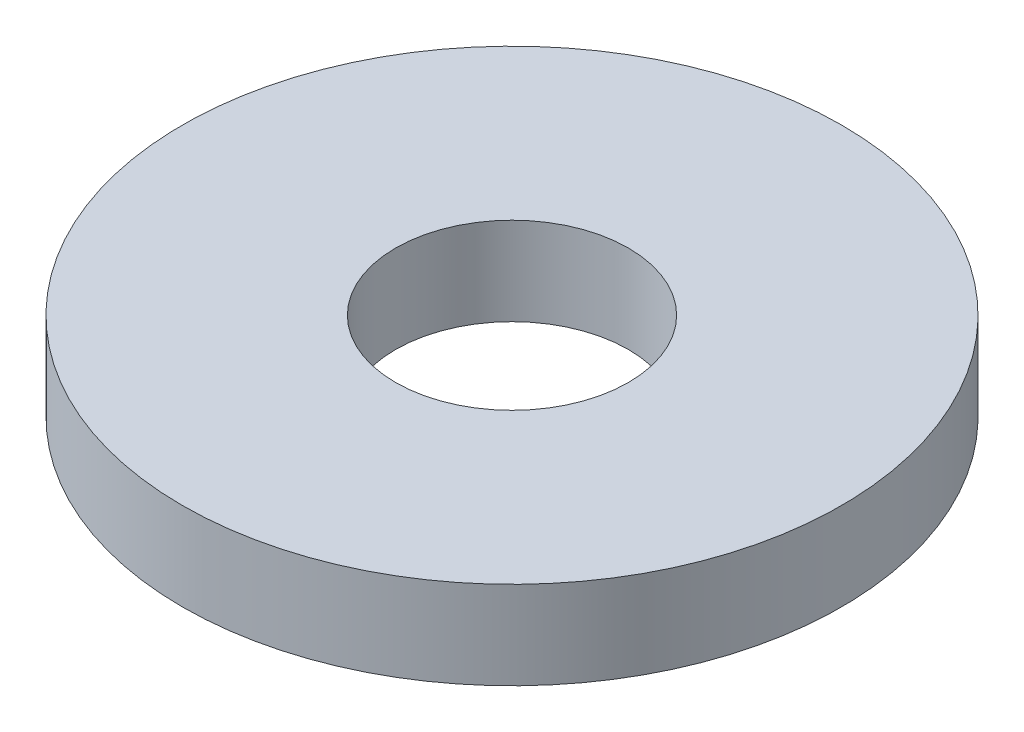
SolidWorks part; units mm, degrees
material "Cast Stainless Steel"
ref_plane "Front Plane" through (0, 0, 0) normal (0, 0, 1) x (1, 0, 0)
ref_plane "Top Plane" through (0, 0, 0) normal (0, 1, 0) x (1, 0, 0)
ref_plane "Right Plane" through (0, 0, 0) normal (1, 0, 0) x (0, 0, -1)
sketch "Sketch1" plane through (0, 0, 0) normal (0, 1, 0) x (1, 0, 0)
  circle A0 centre (0, 0) radius 2.65
  circle A1 centre (0, 0) radius 7.5
  dimension "D1" = 5.3
  dimension "D2" = 15
extrude "Boss-Extrude1" add sketch "Sketch1" along normal blind 2
equation "\"d1\"= 5.3"
equation "\"d2\"= 15"
equation "\"s\" = 2"
equation "\"D2@Sketch1\"=\"d2\""
equation "\"D1@Sketch1\"=\"d1\""
equation "\"D1@Boss-Extrude1\"=\"s\""
